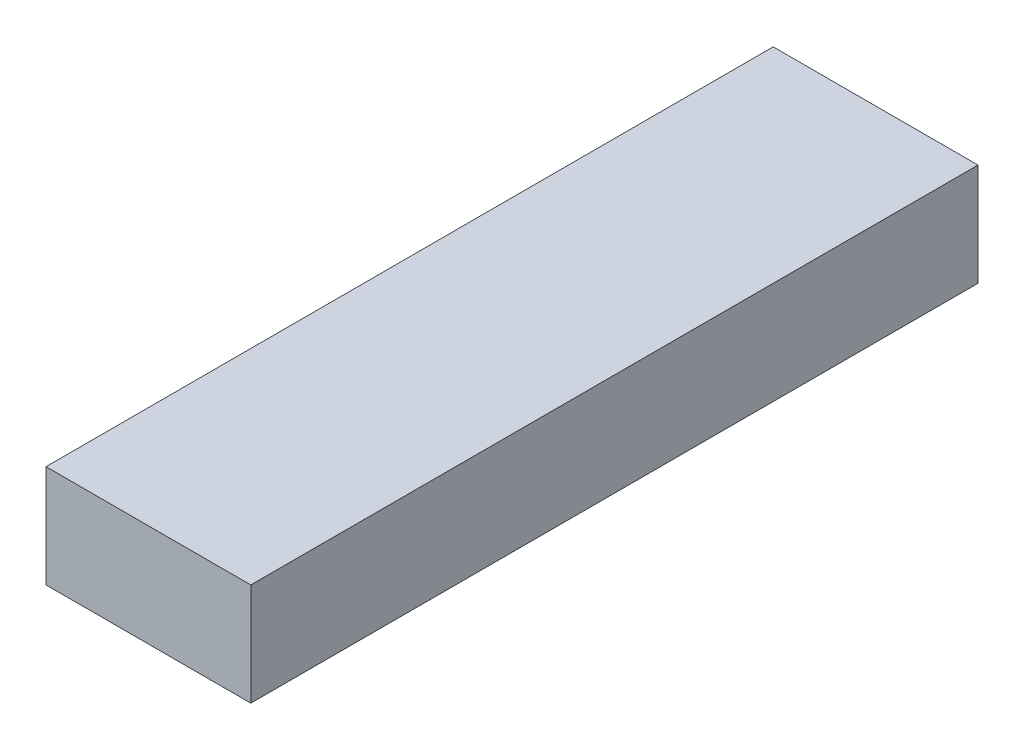
SolidWorks part; units mm, degrees
material "Pine"
ref_plane "X-Y Datum" through (0, 0, 0) normal (0, 0, 1) x (1, 0, 0)
ref_plane "X-Z Datum" through (0, 0, 0) normal (0, 1, 0) x (1, 0, 0)
ref_plane "Y-Z Datum" through (0, 0, 0) normal (1, 0, 0) x (0, 0, -1)
sketch "Sketch1" plane through (0, 0, 0) normal (0, 0, 1) x (1, 0, 0)
  line L1 (-50.8, 25.4) -> (50.8, 25.4)
  line L2 (-50.8, 25.4) -> (-50.8, -25.4)
  line L3 (-50.8, -25.4) -> (50.8, -25.4)
  line L4 (50.8, 25.4) -> (50.8, -25.4)
  line L5 (-50.8, 25.4) -> (50.8, -25.4) construction
  line L6 (-50.8, -25.4) -> (50.8, 25.4) construction
  point P0 (0, 0)
  dimension "D1" = 101.6
  dimension "D2" = 50.8
extrude "Boss-Extrude1" add sketch "Sketch1" along normal blind 360.7757
